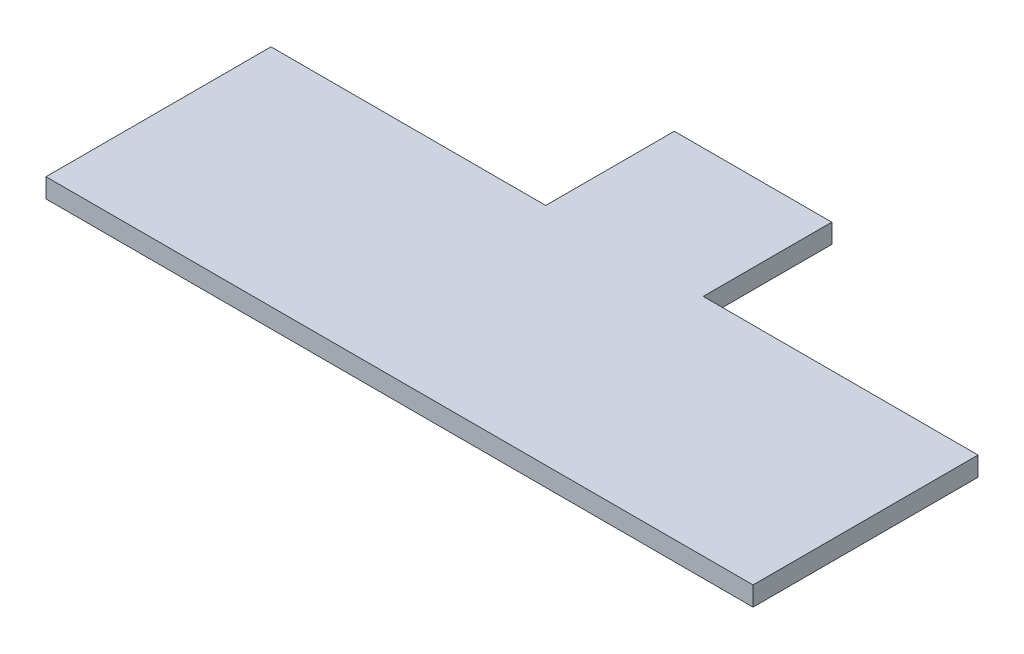
SolidWorks part; units mm, degrees
material "Acrylic (Medium-high impact)"
ref_plane "Front Plane" through (0, 0, 0) normal (0, 0, 1) x (1, 0, 0)
ref_plane "Top Plane" through (0, 0, 0) normal (0, 1, 0) x (1, 0, 0)
ref_plane "Right Plane" through (0, 0, 0) normal (1, 0, 0) x (0, 0, -1)
sketch "Sketch1" plane through (0, 0, 0) normal (0, 1, 0) x (1, 0, 0)
  line L0 (-262.9051, 66.0577) -> (-262.9051, 106.0577)
  line L1 (-348.4051, 66.0577) -> (-262.9051, 66.0577)
  line L2 (-348.4051, 66.0577) -> (-348.4051, -3.9423)
  line L3 (-348.4051, -3.9423) -> (-128.4051, -3.9423)
  line L4 (-128.4051, 66.0577) -> (-128.4051, -3.9423)
  line L5 (-262.9051, 106.0577) -> (-213.9051, 106.0577)
  line L6 (-213.9051, 106.0577) -> (-213.9051, 66.0577)
  line L7 (-213.9051, 66.0577) -> (-128.4051, 66.0577)
  point P8 (-238.4051, -3.9423)
  point P9 (-238.4051, 106.0577)
  dimension "D1" = 70
  dimension "D2" = 220
  dimension "D3" = 0
  dimension "D4" = 49
  dimension "D5" = 40
extrude "Boss-Extrude1" add sketch "Sketch1" along normal blind 6
